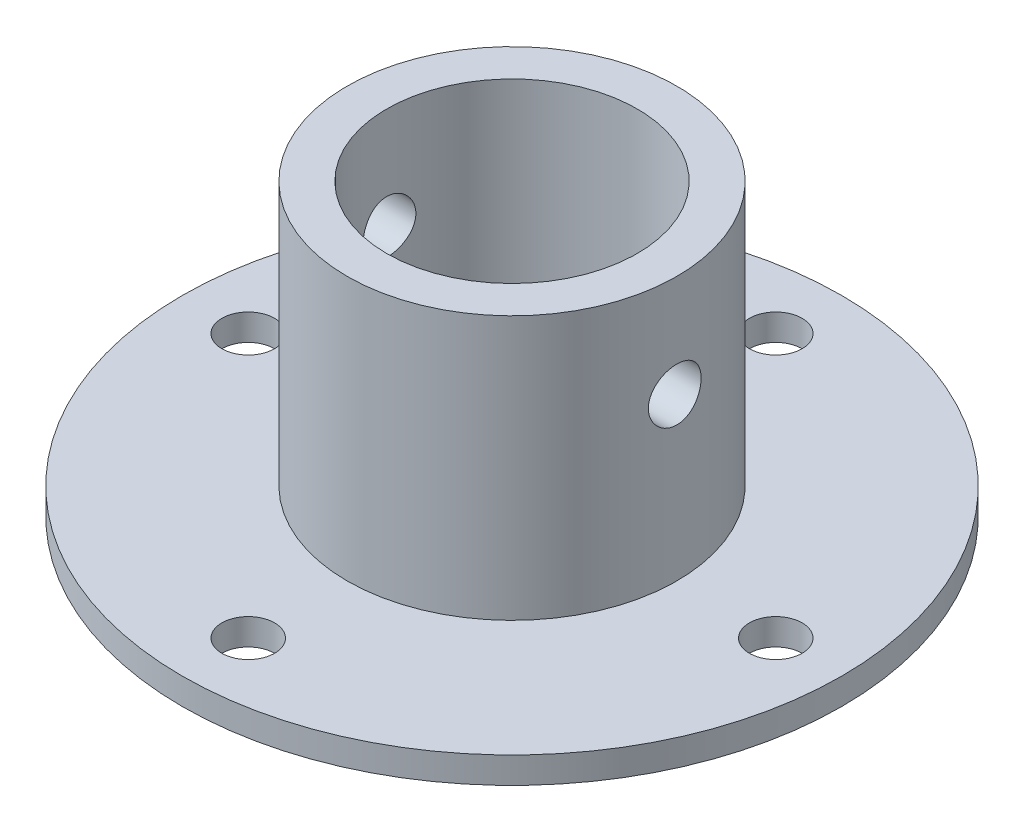
SolidWorks part; units mm, degrees
ref_plane "Front Plane" through (0, 0, 0) normal (0, 0, 1) x (1, 0, 0)
ref_plane "Top Plane" through (0, 0, 0) normal (0, 1, 0) x (1, 0, 0)
ref_plane "Right Plane" through (0, 0, 0) normal (1, 0, 0) x (0, 0, -1)
sketch "Sketch1" plane through (0, 0, 0) normal (0, 1, 0) x (1, 0, 0)
  circle A0 centre (0, 0) radius 25
  circle A1 centre (0, 0) radius 9.5
  dimension "D1" = 50
  dimension "D2" = 19
extrude "Boss-Extrude1" add sketch "Sketch1" along normal blind 2
sketch "Sketch2" plane through (0, 2, 0) normal (0, 1, 0) x (1, 0, 0)
  circle A0 centre (0, 0) radius 9.5
  circle A1 centre (0, 0) radius 12.5
  dimension "D1" = 25
extrude "Boss-Extrude2" add sketch "Sketch2" along normal blind 20
sketch "Sketch3" plane through (0, 2, 0) normal (0, 1, 0) x (1, 0, 0)
  circle A0 centre (0, 20) radius 2
  dimension "D1" = 4
  dimension "D2" = 20
extrude "Cut-Extrude1" cut sketch "Sketch3" against normal blind 25
pattern_circular "CirPattern1" count 4 over 360 about axis through (0, 0, 0) along (0, 1, 0) of "Cut-Extrude1"
sketch "Sketch4" plane through (0, 0, 0) normal (1, 0, 0) x (0, 0, -1)
  line L0 (0, 0) -> (0, 35.68) construction
  circle A0 centre (0, 14.2455) radius 2
  dimension "D1" = 4
extrude "Cut-Extrude2" cut sketch "Sketch4" against normal through all both and the other way through all
